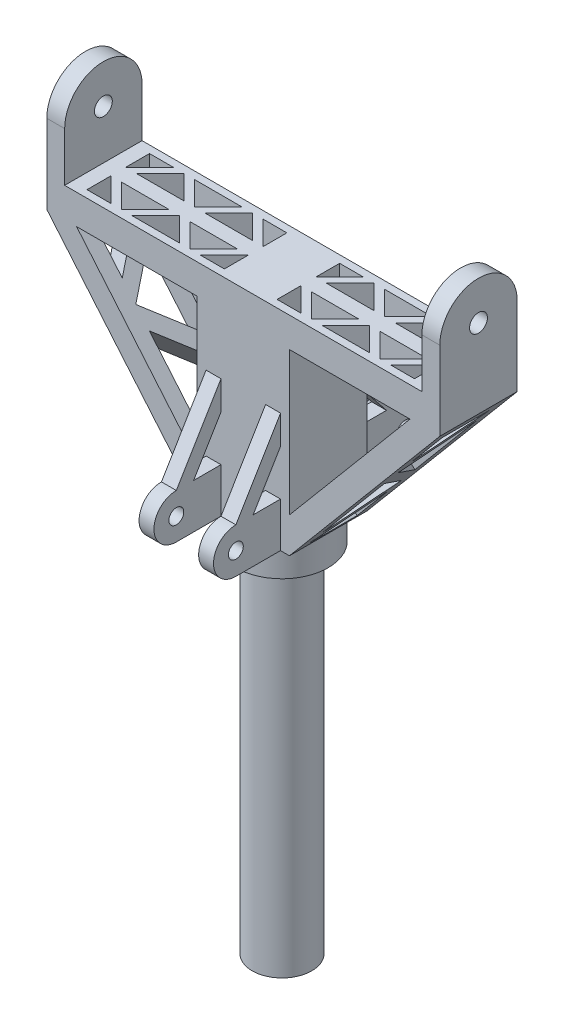
SolidWorks part; units mm, degrees
ref_plane "Front Plane" through (0, 0, 0) normal (0, 0, 1) x (1, 0, 0)
ref_plane "Top Plane" through (0, 0, 0) normal (0, 1, 0) x (1, 0, 0)
ref_plane "Right Plane" through (0, 0, 0) normal (1, 0, 0) x (0, 0, -1)
sketch "Sketch27" plane through (0, 0, 0) normal (0, 0, 1) x (1, 0, 0)
  line L0 (66, 0) -> (-66, 0)
  line L1 (-66, 0) -> (-66, 100)
  line L2 (-66, 100) -> (-60, 100)
  line L3 (-60, 100) -> (-60, 70)
  line L4 (-60, 70) -> (60, 70)
  line L5 (0, 0) -> (0, 82.1741) construction
  line L6 (60, 100) -> (60, 70)
  line L7 (66, 100) -> (60, 100)
  line L8 (66, 0) -> (66, 100)
  point P10 (0, 0)
  point P11 (0, 70)
  dimension "D1" = 120
  dimension "D2" = 6
  dimension "D3" = 100
  dimension "D4" = 30
extrude "Tykkelse leddfester og bredde/høyde selve modellen" add sketch "Sketch27" along normal mid plane 26
sketch "Sketch28" plane through (0, 0, 0) normal (0, -1, 0) x (1, 0, 0)
  line L0 (-66, -13) -> (66, -13) construction
  line L1 (66, 13) -> (66, -13) construction
  circle A1 centre (0, 0) radius 10.5
  circle A2 centre (0, 0) radius 15.5
  point P6 (0, -13)
  point P9 (66, 0)
  dimension "D1" = 21
  dimension "D2" = 5
extrude "Hull til lårben/karbonfiberrør" add sketch "Sketch28" along normal blind 10
sketch "Sketch29" plane through (66, 0, 0) normal (1, 0, 0) x (0, 0, -1)
  line L0 (-13, 100) -> (13, 100) construction
  line L1 (-13, 86.5) -> (-13, 71.5)
  line L2 (13, 86.5) -> (13, 71.5)
  line L4 (-14, 101) -> (0, 101)
  line L8 (0, 86.5) -> (0, 83.5) construction
  line L9 (0, 100) -> (0, 99.5) construction
  line L13 (-13, 71.5) -> (-14, 71.5)
  line L14 (-14, 71.5) -> (-14, 101)
  line L18 (13, 71.5) -> (14, 71.5)
  line L19 (14, 71.5) -> (14, 101)
  line L20 (14, 101) -> (0, 101)
  circle A0 centre (0, 86.5) radius 3
  arc A1 (13, 86.5) -> (-13, 86.5) centre (0, 86.5) ccw
  circle A2 centre (0, 86.5) radius 13 construction
  point P4 (0, 100)
  point P14 (-7, 101)
  dimension "D1" = 6
  dimension "D3" = 15
  dimension "D4" = 0.5
  dimension "D5" = 1
  dimension "D6" = 1
  dimension "D2" = 10
extrude "Skruehull leddfester" cut sketch "Sketch29" against normal through all both and the other way through all
sketch "Fasong (mønster på selve kroppen)" plane through (0, 0, 13) normal (0, 0, 1) x (1, 0, 0)
  line L0 (-66, 60) -> (-15.5, 0)
  line L1 (-66, 86.5) -> (-66, 0) construction
  line L2 (-15.5, 0) -> (-66, 0)
  line L3 (-66, 0) -> (-66, 60)
  line L4 (-60, 70) -> (-66, 70) construction
  line L5 (0, 0) -> (0, 49.2612) construction
  line L6 (15.5, 0) -> (66, 0)
  line L7 (66, 60) -> (15.5, 0)
  line L8 (66, 0) -> (66, 60)
  line L9 (-15.5, 0) -> (-15.5, 60) construction
  line L11 (15.5, 0) -> (15.5, 60) construction
  line L12 (-66, 60) -> (-56, 60) construction
  line L13 (-56, 60) -> (-15.5, 11.8812)
  line L14 (-56, 60) -> (-15.5, 60)
  line L15 (-15.5, 60) -> (-15.5, 11.8812)
  line L16 (56, 60) -> (15.5, 60)
  line L17 (56, 60) -> (15.5, 11.8812)
  line L18 (15.5, 60) -> (15.5, 11.8812)
  dimension "D1" = 10
  dimension "D2" = 10
  dimension "D3" = 31
sketch "Sketch33" plane through (0, 0, -13) normal (0, 0, -1) x (-1, 0, 0)
  line L4 (8.441, 0) -> (-8.441, 0) construction
  line L5 (-3.5, 20) -> (-3.5, 0)
  line L6 (-3.5, 0) -> (-8.5, 0)
  line L7 (-8.5, 0) -> (-8.5, 20)
  line L8 (-8.5, 20) -> (-3.5, 20)
  line L9 (0, 0) -> (0, 33.6157) construction
  line L10 (0, 0) -> (0, 49.2612) construction
  line L11 (8.5, 0) -> (8.5, 20)
  line L12 (3.5, 0) -> (8.5, 0)
  line L13 (3.5, 20) -> (3.5, 0)
  line L14 (8.5, 20) -> (3.5, 20)
  dimension "D1" = 5
  dimension "D2" = 20
  dimension "D3" = 7
extrude "Bredde og avstand stempelende" add sketch "Sketch33" along normal blind 60
sketch "Rod-ende, justere lengden (altså feste til største sylinder)" plane through (8.5, 0, 0) normal (1, 0, 0) x (0, 0, -1)
  line L0 (13, 20) -> (13, 0) construction
  line L5 (43, -1) -> (74, -1)
  line L6 (74, -1) -> (74, 21)
  line L7 (74, 21) -> (43, 21)
  line L9 (73, 0) -> (13, 0) construction
  line L11 (73, 20) -> (73, 0) construction
  line L12 (73, 20) -> (13, 20) construction
  line L13 (33, 1) -> (13, 1)
  line L14 (13, 0) -> (13, 86.5) construction
  line L15 (13, 1) -> (13, -1)
  line L16 (13, -1) -> (43, -1)
  line L17 (43, 21) -> (13, 21)
  line L18 (13, 21) -> (13, 19)
  line L19 (13, 19) -> (33, 19)
  circle A0 centre (33, 10) radius 3
  arc A1 (33, 1) -> (33, 19) centre (33, 10) ccw
  circle A2 centre (33, 10) radius 9 construction
  point P6 (13, 10)
  dimension "D1" = 6
  dimension "D3" = 20
  dimension "D4" = 1
  dimension "D5" = 1
  dimension "D6" = 1
  dimension "D2" = 6
sketch "Sketch39" plane through (0, 0, 13) normal (0, 0, 1) x (1, 0, 0)
  line L1 (-7.5, 0) -> (-7.5, 15)
  line L3 (-7.5, 15) -> (-12.5, 15)
  line L4 (-12.5, 15) -> (-12.5, 0)
  line L5 (-12.5, 0) -> (-7.5, 0)
  line L11 (0, 0) -> (0, 49.2612) construction
  line L12 (0, 0) -> (0, 21.5969) construction
  line L13 (12.5, 0) -> (7.5, 0)
  line L14 (12.5, 15) -> (12.5, 0)
  line L15 (7.5, 15) -> (12.5, 15)
  line L16 (7.5, 0) -> (7.5, 15)
  line L17 (-8.441, 0) -> (8.441, 0) construction
  dimension "D1" = 15
  dimension "D2" = 5
  dimension "D3" = 7.5
extrude "Cut-Extrude4" cut sketch "Fasong (mønster på selve kroppen)" against normal through all
sketch "Sketch40" plane through (-9.0728, -7.6363, 0) normal (-0.7651, -0.6439, 0) x (0, 0, 1)
  line L0 (0, 88.4046) -> (0, 35.3376) construction
  line L1 (-13, 88.4046) -> (13, 88.4046) construction
  line L2 (-8, 81.9046) -> (8, 81.9046)
  line L3 (-13, 9.9811) -> (-13, 88.4046) construction
  line L4 (-8, 81.9046) -> (8, 65.9046)
  line L6 (-8, 74.8335) -> (8, 58.8335)
  line L8 (-8, 42.8335) -> (8, 58.8335)
  line L9 (8, 81.9046) -> (8, 65.9046)
  line L10 (-8, 42.8335) -> (-8, 74.8335)
  line L13 (8, 19.7625) -> (-8, 35.7625)
  line L16 (8, 51.7625) -> (-8, 35.7625)
  line L18 (8, 19.7625) -> (8, 51.7625)
  line L19 (-8, 28.6914) -> (8, 12.6914)
  line L20 (8, 12.6914) -> (-8, 12.6914)
  line L21 (-8, 12.6914) -> (-8, 28.6914)
  line L22 (-13, 9.9811) -> (0, 9.9811) construction
  point P8 (0, 81.9046)
  dimension "D1" = 6.5
  dimension "D2" = 5
  dimension "D3" = 45
  dimension "D4" = 90
  dimension "D5" = 5
  dimension "D6" = 5
  dimension "D7" = 90
  dimension "D8" = 5
  dimension "D9" = 2.7103
extrude "Sidemønster" cut sketch "Sketch40" against normal up to vertex (7.6508 mm away)
sketch "Sketch42" plane through (9.0728, -7.6363, 0) normal (0.7651, -0.6439, 0) x (0, 0, -1)
  line L3 (0, 88.4046) -> (0, 81.9046) construction
  line L4 (13, 88.4046) -> (-13, 88.4046) construction
  line L5 (8, 81.9046) -> (-8, 81.9046)
  line L6 (-13, 88.4046) -> (-13, 9.9811) construction
  line L7 (-8, 81.9046) -> (-8, 65.9046)
  line L8 (-8, 65.9046) -> (8, 81.9046)
  line L9 (8, 74.8335) -> (-8, 58.8335)
  line L11 (8, 42.8335) -> (8, 74.8335)
  line L12 (8, 42.8335) -> (-8, 58.8335)
  line L13 (-8, 51.7625) -> (8, 35.7625)
  line L15 (-8, 19.7625) -> (-8, 51.7625)
  line L16 (-8, 19.7625) -> (8, 35.7625)
  line L17 (8, 28.6914) -> (-8, 12.6914)
  line L18 (-8, 12.6914) -> (8, 12.6914)
  line L19 (8, 12.6914) -> (8, 28.6914)
  point P8 (0, 88.4046)
  point P11 (0, 81.9046)
  dimension "D1" = 6.5
  dimension "D2" = 5
  dimension "D3" = 45
  dimension "D4" = 5
  dimension "D5" = 45
  dimension "D6" = 45
  dimension "D7" = 5
  dimension "D9" = 5
extrude "Sidemønster 2" cut sketch "Sketch42" against normal up to vertex (7.6508 mm away)
sketch "Sketch44" plane through (0, 0, 0) normal (0, -1, 0) x (1, 0, 0)
  circle A0 centre (0, 0) radius 10.5
  dimension "D1" = 21
extrude "Utvidet lårbenhull inn i selve kroppen" cut sketch "Sketch44" against normal blind 40
sketch "Sketch45" plane through (0, 70, 0) normal (0, 1, 0) x (1, 0, 0)
  line L3 (-39.9289, 10.5) -> (-31.9289, 2.5)
  line L5 (-23.9289, 10.5) -> (-39.9289, 10.5)
  line L6 (-16.8579, 10.5) -> (-8.8579, 2.5)
  line L7 (0, 0) -> (0, 11.265) construction
  line L8 (0, 0) -> (-55, 0) construction
  line L9 (-60, -13) -> (-60, 13) construction
  line L10 (-55, 2.5) -> (-55, 10.5)
  line L11 (-55, 10.5) -> (-47, 10.5)
  line L12 (-47, 10.5) -> (-55, 2.5)
  line L13 (60, 13) -> (-60, 13) construction
  line L14 (-43.4645, 10.5) -> (-51.4645, 2.5)
  line L15 (-51.4645, 2.5) -> (-35.4645, 2.5)
  line L17 (-43.4645, 10.5) -> (-35.4645, 2.5)
  line L18 (-23.9289, 10.5) -> (-31.9289, 2.5)
  line L19 (-20.3934, 10.5) -> (-28.3934, 2.5)
  line L20 (-28.3934, 2.5) -> (-12.3934, 2.5)
  line L22 (-20.3934, 10.5) -> (-12.3934, 2.5)
  line L23 (-8.8579, 2.5) -> (-8.8579, 10.5)
  line L24 (-8.8579, 10.5) -> (-16.8579, 10.5)
  line L25 (-8.8579, -2.5) -> (-8.8579, -10.5)
  line L26 (-16.8579, -10.5) -> (-8.8579, -2.5)
  line L27 (-8.8579, -10.5) -> (-16.8579, -10.5)
  line L28 (-20.3934, -10.5) -> (-12.3934, -2.5)
  line L29 (-28.3934, -2.5) -> (-12.3934, -2.5)
  line L30 (-20.3934, -10.5) -> (-28.3934, -2.5)
  line L31 (-23.9289, -10.5) -> (-31.9289, -2.5)
  line L32 (-23.9289, -10.5) -> (-39.9289, -10.5)
  line L33 (-39.9289, -10.5) -> (-31.9289, -2.5)
  line L34 (-43.4645, -10.5) -> (-35.4645, -2.5)
  line L35 (-51.4645, -2.5) -> (-35.4645, -2.5)
  line L36 (-43.4645, -10.5) -> (-51.4645, -2.5)
  line L37 (-55, -10.5) -> (-47, -10.5)
  line L38 (-55, -2.5) -> (-55, -10.5)
  line L39 (-47, -10.5) -> (-55, -2.5)
  line L40 (8.8579, 2.5) -> (8.8579, 10.5)
  line L41 (16.8579, 10.5) -> (8.8579, 2.5)
  line L42 (8.8579, 10.5) -> (16.8579, 10.5)
  line L43 (16.8579, -10.5) -> (8.8579, -2.5)
  line L44 (8.8579, -10.5) -> (16.8579, -10.5)
  line L45 (8.8579, -2.5) -> (8.8579, -10.5)
  line L46 (20.3934, -10.5) -> (28.3934, -2.5)
  line L47 (28.3934, -2.5) -> (12.3934, -2.5)
  line L48 (20.3934, -10.5) -> (12.3934, -2.5)
  line L49 (20.3934, 10.5) -> (12.3934, 2.5)
  line L50 (28.3934, 2.5) -> (12.3934, 2.5)
  line L51 (20.3934, 10.5) -> (28.3934, 2.5)
  line L52 (23.9289, 10.5) -> (31.9289, 2.5)
  line L53 (23.9289, 10.5) -> (39.9289, 10.5)
  line L54 (39.9289, 10.5) -> (31.9289, 2.5)
  line L55 (23.9289, -10.5) -> (39.9289, -10.5)
  line L56 (39.9289, -10.5) -> (31.9289, -2.5)
  line L57 (23.9289, -10.5) -> (31.9289, -2.5)
  line L58 (43.4645, -10.5) -> (51.4645, -2.5)
  line L59 (51.4645, -2.5) -> (35.4645, -2.5)
  line L60 (43.4645, -10.5) -> (35.4645, -2.5)
  line L61 (55, -2.5) -> (55, -10.5)
  line L62 (47, -10.5) -> (55, -2.5)
  line L63 (55, -10.5) -> (47, -10.5)
  line L64 (43.4645, 10.5) -> (35.4645, 2.5)
  line L65 (51.4645, 2.5) -> (35.4645, 2.5)
  line L66 (43.4645, 10.5) -> (51.4645, 2.5)
  line L67 (55, 10.5) -> (47, 10.5)
  line L68 (55, 2.5) -> (55, 10.5)
  line L69 (47, 10.5) -> (55, 2.5)
  dimension "D1" = 5
  dimension "D2" = 2.5
  dimension "D3" = 2.5
  dimension "D4" = 45
  dimension "D5" = 2.5
  dimension "D6" = 45
  dimension "D7" = 2.5
  dimension "D8" = 45
  dimension "D9" = 2.5
  dimension "D10" = 45
  dimension "D11" = 2.5
extrude "Mønster topp" cut sketch "Sketch45" against normal up to vertex (10 mm away)
extrude "Stempelende av største sylinder " cut sketch "Rod-ende, justere lengden (altså feste til største sylinder)" against normal through all both and the other way through all
extrude "Sylinderfeste, selve den lille sylinderen " add sketch "Sketch39" along normal blind 25
sketch "Sketch46" plane through (8.5, 0, 0) normal (1, 0, 0) x (0, 0, -1)
  line L2 (13, 60) -> (13, 0) construction
  line L3 (13, 35.9961) -> (26.5969, 19)
  line L4 (33, 19) -> (13, 19) construction
  line L5 (26.5969, 19) -> (33, 19)
  line L6 (33, 19) -> (13, 44)
  line L7 (13, 44) -> (13, 35.9961)
  line M3 (33, 19) -> (13, 19)
  dimension "D1" = 5
  dimension "D2" = 25
extrude "Støtter største sylinder 1" add sketch "Sketch46" against normal blind 5 contours L6 L7 L3 M3
sketch "Sketch47" plane through (-8.5, 0, 0) normal (-1, 0, 0) x (0, 0, 1)
  line L0 (-33, 19) -> (-13, 44)
  line L1 (-13, 0) -> (-13, 60) construction
  line L2 (-13, 44) -> (-13, 35.9961) construction
  line L3 (-13, 44) -> (-13, 35.9961)
  line L4 (-13, 35.9961) -> (-26.5969, 19)
  line L5 (-13, 19) -> (-33, 19) construction
  line L6 (-13, 35.9961) -> (-26.5969, 19) construction
  line L7 (-26.5969, 19) -> (-33, 19)
extrude "Støtter største sylinder 2" add sketch "Sketch47" against normal blind 5
sketch "Sketch48" plane through (-12.5, 0, 0) normal (-1, 0, 0) x (0, 0, 1)
  line L0 (13, 15) -> (13, 0) construction
  line L1 (28, 0) -> (13.1798, 0)
  line L2 (13.1798, 0) -> (13.1798, -1)
  line L3 (13.1798, -1) -> (39, -1)
  line L4 (39, -1) -> (39, 16)
  line L5 (39, 16) -> (13, 16)
  line L6 (13, 0) -> (13, 60) construction
  line L7 (13, 16) -> (13, 15)
  line L8 (13, 15) -> (28, 15)
  line L9 (38, 15) -> (13, 15) construction
  line L10 (38, 15) -> (38, 0) construction
  circle A0 centre (28, 7.5) radius 2.5
  arc A1 (28, 0) -> (28, 15) centre (28, 7.5) ccw
  circle A2 centre (28, 7.5) radius 7.5 construction
  point P6 (13, 7.5)
  dimension "D1" = 5
  dimension "D3" = 1
  dimension "D4" = 1
  dimension "D5" = 1
  dimension "D6" = 15
  dimension "D2" = 5
extrude "Sylinderfeste, liten sylinder" cut sketch "Sketch48" against normal through all both and the other way through all
sketch "Sketch49" plane through (-12.5, 0, 0) normal (-1, 0, 0) x (0, 0, 1)
  line L0 (28, 15) -> (13, 40)
  line L1 (13, 0) -> (13, 60) construction
  line L2 (13, 40) -> (13, 30.2817)
  line L3 (22.169, 15) -> (28, 15)
  line L4 (13, 30.2817) -> (22.169, 15)
  dimension "D1" = 25
  dimension "D2" = 5
sketch "Sketch50" plane through (12.5, 0, 0) normal (1, 0, 0) x (0, 0, -1)
  line L0 (-28, 15) -> (-22.169, 15)
  line L1 (-22.169, 15) -> (-13, 30.2817)
  line L2 (-13, 30.2817) -> (-13, 40)
  line L3 (-13, 40) -> (-28, 15)
extrude "Boss-Extrude11" add sketch "Sketch49" against normal blind 5
extrude "Boss-Extrude12" add sketch "Sketch50" against normal blind 5 contours L3 L0 L1 L2
sketch "Sketch51" plane through (0, 40, 0) normal (0, -1, 0) x (1, 0, 0)
  circle A0 centre (0, 0) radius 10
  dimension "D1" = 20
extrude "TIL ASSEMBLY - SLETT FØR PRINTING" add sketch "Sketch51" along normal blind 170
